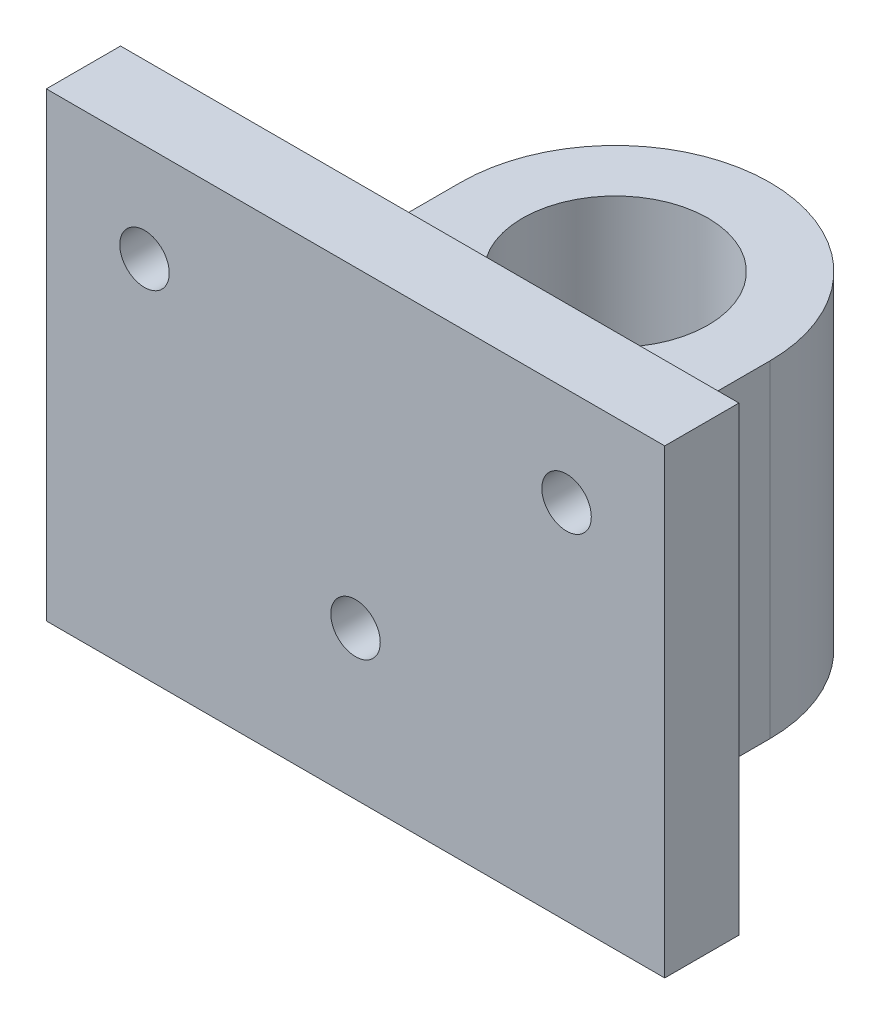
SolidWorks part; units mm, degrees
ref_plane "Front Plane" through (0, 0, 0) normal (0, 0, 1) x (1, 0, 0)
ref_plane "Top Plane" through (0, 0, 0) normal (0, 1, 0) x (1, 0, 0)
ref_plane "Right Plane" through (0, 0, 0) normal (1, 0, 0) x (0, 0, -1)
sketch "Profile-Sketch1" plane through (0, 0, 0) normal (0, 1, 0) x (1, 0, 0)
  line L0 (-25, -21) -> (25, -21)
  line L1 (25, -21) -> (25, -15)
  line L2 (-25, -21) -> (-25, -15)
  line L3 (-25, -15) -> (-22.5, -15)
  line L4 (-12.5, -5) -> (-12.5, 0)
  line L5 (25, -15) -> (22.5, -15)
  line L6 (12.5, -5) -> (12.5, 0)
  circle A0 centre (0, 0) radius 7.5
  arc A6 (12.5, 0) -> (-12.5, 0) centre (0, 0) ccw
  arc A7 (22.5, -15) -> (12.5, -5) centre (22.5, -5) cw
  arc A8 (-12.5, -5) -> (-22.5, -15) centre (-22.5, -5) cw
  dimension "D1" = 15
  dimension "D2" = 12.5
  dimension "D7" = 10
  dimension "D3" = 50
  dimension "D4" = 25
  dimension "D5" = 21
  dimension "D6" = 6
extrude "Profile-Boss-Extrude2" add sketch "Profile-Sketch1" along normal blind 37.2599
sketch "FasteningHoleSketch3" plane through (0, 0, 21) normal (0, 0, 1) x (1, 0, 0)
  line L0 (25, 37.2599) -> (25, 0) construction
  line L1 (-25, 37.2599) -> (-25, 0) construction
  line L2 (-25, 0) -> (25, 0) construction
  circle A2 centre (-17.0625, 29.3224) radius 2
  circle A3 centre (17.0625, 29.3224) radius 2
  dimension "D3" = 4
  dimension "D6" = 7.9375
  dimension "D2" = 29.3224
  dimension "D1" = 7.9375
extrude "FasteningHoleCut-Extrude8" cut sketch "FasteningHoleSketch3" against normal through all
sketch "LM8UUFasteningHoleSketch5" plane through (0, 0, 21) normal (0, 0, 1) x (1, 0, 0)
  line L0 (25, 37.2599) -> (25, 0) construction
  line L1 (-25, 0) -> (25, 0) construction
  line L2 (-25, 37.2599) -> (25, 37.2599) construction
  circle A0 centre (0, 12) radius 2
  circle A1 centre (-17.0625, 29.3224) radius 2 construction
  dimension "D1" = 25
  dimension "D2" = 12
  dimension "D3" = 25.2599
extrude "LM8UUFasteningHoleCut-Extrude9" cut sketch "LM8UUFasteningHoleSketch5" against normal through all
sketch "TopKnotchSketch2" plane through (0, 37.2599, 0) normal (0, 1, 0) x (1, 0, 0)
  line L0 (-25, -15) -> (25, -15)
  line L1 (-25, -15) -> (-25, 12.5)
  line L2 (25, -15) -> (25, 12.5)
  line L3 (-25, 12.5) -> (25, 12.5)
  line L4 (-25, -15) -> (-25, -21) construction
  arc A0 (12.5, 0) -> (-12.5, 0) centre (0, 0) ccw construction
extrude "TopKnotchCut-Extrude1" cut sketch "TopKnotchSketch2" against normal blind 10.8
sketch "RightZAxisMicroSwitchSketch2" plane through (0, 0, 0) normal (0, -1, 0) x (1, 0, 0)
  line L1 (-11.1, 0) -> (-13.9, 0)
  line L3 (-11.1, 12.85) -> (-13.9, 12.85)
  line L5 (-13.9, 0) -> (-13.9, 10.086)
  line L6 (-13.9, 12.85) -> (-16.3426, 12.85)
  line L7 (-16.3426, 12.85) -> (-13.9, 10.086)
  line L8 (-11.1, 12.85) -> (-11.1, 0)
  line L9 (-12.5, 0) -> (-12.5, 5) construction
  dimension "D1" = 2.8
  dimension "D3" = 12.85
  dimension "D2" = 1.4
extrude "RightZAxisMicroSwitchCut-Extrude1" cut sketch "RightZAxisMicroSwitchSketch2" against normal blind 12.05
sketch "MicroSwitchMountingHolesSketch1" plane through (-11.1, 0, 0) normal (-1, 0, 0) x (0, 0, 1)
  line L0 (0, 26.4599) -> (0, 0) construction
  line L1 (12.85, 12.05) -> (12.85, 0) construction
  line L2 (0, 12.05) -> (12.85, 12.05) construction
  circle A0 centre (3.25, 5.05) radius 1.5
  circle A1 centre (9.6, 5.05) radius 1.5
  dimension "D4" = 3
  dimension "D1" = 3.25
  dimension "D2" = 3.25
  dimension "D3" = 7
extrude "MicroSwitchMountingHolesCut-Extrude1" cut sketch "MicroSwitchMountingHolesSketch1" against normal blind 3.1
equation "\"RailThickness\"= .125in'Spec"
equation "\"LM8UUDiameter\"= 15mm"
equation "\"MidLeftOrRightSideRailHeight\"= 2.0in"
equation "\"RodStabilizerLength\"= 50mm"
equation "\"HoleOffsetFromEdge\"= \"RailThickness\" * 2.5"
equation "\"StepperMountingHoleOffsetFromItsSide\"= 5.5mm'Spec"
equation "\"StepperMountingHoleOffsetFromLeftOrRightSide\"= \"StepperMountingHoleOffsetFromItsSide\" + \"RailThickness\""
equation "\"StepperMountingHoleDistance\"= 31mm'Spec"
equation "\"LM8UUHeight\"= 24mm'Spec"
equation "\"ZAxisLeadScrewLength\"= 200mm"
equation "\"LegHeight\"= 70mm'Space needed for PSU/Stepper/Electronics"
equation "\"V1 BottomOfLowerRail\"= \"LegHeight\""
equation "\"StepperShaftLength\"= 24mm'Pulley will be attached to the end"
equation "\"V2 ToBedAtTopOfZAxis\"= \"V1 BottomOfLowerRail\" - \"LowerEnclosureThickness\" + \"StepperShaftLength\" + \"ZAxisLeadScrewLength\" - \"LM8UUHeight\" / 2'Equals 277"
equation "\"HotEndToTopOfXAxisGB\"= 71.68487mm'Equals 71.68487. Measured after installed onto X-Axis linear rail guide block"
equation "\"TopOfGBToBottomOfLinearRail\"= \"LinearGBWidth\" / 2 + \"LinearRailWidth\" / 2'Equals 19.5"
equation "\"LinearGBWidth\"= 27mm'Spec"
equation "\"V5 ToBottomOfXAxisLinearRail\"= \"V4 ToTopOfBuildPlate/HotEndTip\" + \"HotEndToTopOfXAxisGB\" - \"TopOfGBToBottomOfLinearRail\"'Equals 352.18487"
equation "\"LinearRailWidth\"= 12mm'Spec"
equation "\"V6 ToMiddleOfYAxisGantryBlock\"= \"V5 ToBottomOfXAxisLinearRail\" - \"GABHeight\" / 2'Equals 334.18487"
equation "\"GABUpperHeight\"= 4mm"
equation "\"GABMidWallHeight\"= 28mm'Must equal 28 or changes alignment"
equation "\"BedToBuildPlateStandoffLength\"= 15mm"
equation "\"BuildPlateHeight\"= 8mm'Spec"
equation "\"V4 ToTopOfBuildPlate/HotEndTip\"= \"V2 ToBedAtTopOfZAxis\" + \"BedToBuildPlateStandoffLength\" + \"BuildPlateHeight\""
equation "\"RodStabilizerHeight\"= \"V8 ToBottomOfMidSideRail\" - \"V2 ToBedAtTopOfZAxis\" + \"HoleOffsetFromEdge\" * 2"
equation "\"LowerEnclosureThickness\"= 5mm"
equation "\"D1@Profile-Sketch1\" = \"LM8UUDiameter\""
equation "\"D3@Profile-Sketch1\" = \"RodStabilizerLength\""
equation "\"D4@Profile-Sketch1\" = \"RodStabilizerLength\" / 2"
equation "\"RodStabilizerWidthFromMidRailToZAxisRodCenter\"= \"StepperMountingHoleOffsetFromLeftOrRightSide\" + \"StepperMountingHoleDistance\" / 2 - \"RailThickness\""
equation "\"StandardWallThickness\"= 3mm"
equation "\"D6@Profile-Sketch1\" = \"StandardWallThickness\" * 2"
equation "\"D1@Profile-Boss-Extrude2\"= \"RodStabilizerHeight\""
equation "\"D6@FasteningHoleSketch3\"=\"HoleOffsetFromEdge\""
equation "\"D2@LM8UUFasteningHoleSketch5\"=\"LM8UUHeight\"/2"
equation "\"V8 ToTopOfMidSideRail\"= \"V6 ToMiddleOfYAxisGantryBlock\" + \"MidSideRailVerticalOffset\"'Equals 349.18487"
equation "\"D5@Profile-Sketch1\"=\"RodStabilizerWidthFromMidRailToZAxisRodCenter\""
equation "\"RodStabilizerMountingHoleYOffsetFromBottom\"= \"RodStabilizerHeight\" - \"HoleOffsetFromEdge\""
equation "\"D2@FasteningHoleSketch3\"=\"RodStabilizerMountingHoleYOffsetFromBottom\""
equation "\"D3@FasteningHoleSketch3\"=\"M3HeatInsertHoleDiameter\""
equation "\"GABLowerHeight\"= 4mm"
equation "\"GABHeight\"= \"GABLowerHeight\" + \"GABMidWallHeight\" + \"GABUpperHeight\""
equation "\"V8 ToBottomOfMidSideRail\"= \"V8 ToTopOfMidSideRail\" - \"MidLeftOrRightSideRailHeight\"'Equals 298.38487"
equation "\"D1@LM8UUFasteningHoleSketch5\"=\"RodStabilizerLength\"/2"
equation "\"MidSideRailVerticalOffset\"= \"LinearRailWidth\" + 3mm'Allows space for RodStabilizer to attach to bottom of MidSideRail"
equation "\"M3HeatInsertHoleDiameter\"= 4mm'Spec"
equation "\"MicroSwitchLength\"= 12.85mm"
equation "\"MicroSwitchHeight\"= 6.55mm"
equation "\"MicroSwitchMountHoleOffsetFromSide\"= 3.25mm"
equation "\"MicroSwitchDepth\"= 2.8mm"
equation "\"MicroSwitchTerminalHeight\"= 3.5mm"
equation "\"M2HeatInsertHoleDiameter\"= 3mm'Spec"
equation "\"MicroSwitchMountHoleOffsetFromBottom\"= 1.5mm"
equation "\"MicroSwitchExtraMountingHeight\"= 2mm"
equation "\"M2HeatInsertHoleDepth\"= 3.1mm'Spec"
equation "\"GABDistanceFromBackToFirstPulley\"= 13.5mm"
equation "\"GABPulleyDDistanceBetween\"= 12.5mm'From the100"
equation "\"GABDistanceFromPulleyToFront\"= 8mm"
equation "\"GABDepth\"= \"GABDistanceFromBackToFirstPulley\" + \"GABPulleyDDistanceBetween\" + \"GABDistanceFromPulleyToFront\""
equation "\"LinearGBWithRailDepth\"= 12.75mm'Spec"
equation "\"GABDepthPlusLinearRail\"= \"GABDepth\" + \"LinearGBWithRailDepth\""
equation "\"D1@TopKnotchCut-Extrude1\" = \"MicroSwitchDepth\" + 8mm"
equation "\"D1@RightZAxisMicroSwitchSketch2\" = \"MicroSwitchDepth\""
equation "\"D3@RightZAxisMicroSwitchSketch2\" = \"MicroSwitchLength\""
equation "\"D1@RightZAxisMicroSwitchCut-Extrude1\"=\"MicroSwitchHeight\" + \"MicroSwitchTerminalHeight\" + \"MicroSwitchExtraMountingHeight\""
equation "\"D2@RightZAxisMicroSwitchSketch2\"=\"MicroSwitchDepth\"/2"
equation "\"D1@MicroSwitchMountingHolesSketch1\" = \"MicroSwitchMountHoleOffsetFromSide\""
equation "\"D2@MicroSwitchMountingHolesSketch1\" = \"MicroSwitchMountHoleOffsetFromSide\""
equation "\"D3@MicroSwitchMountingHolesSketch1\" = \"MicroSwitchExtraMountingHeight\" + \"MicroSwitchTerminalHeight\" + \"MicroSwitchMountHoleOffsetFromBottom\""
equation "\"D4@MicroSwitchMountingHolesSketch1\" = \"M2HeatInsertHoleDiameter\""
equation "\"D1@MicroSwitchMountingHolesCut-Extrude1\"=\"M2HeatInsertHoleDepth\""
